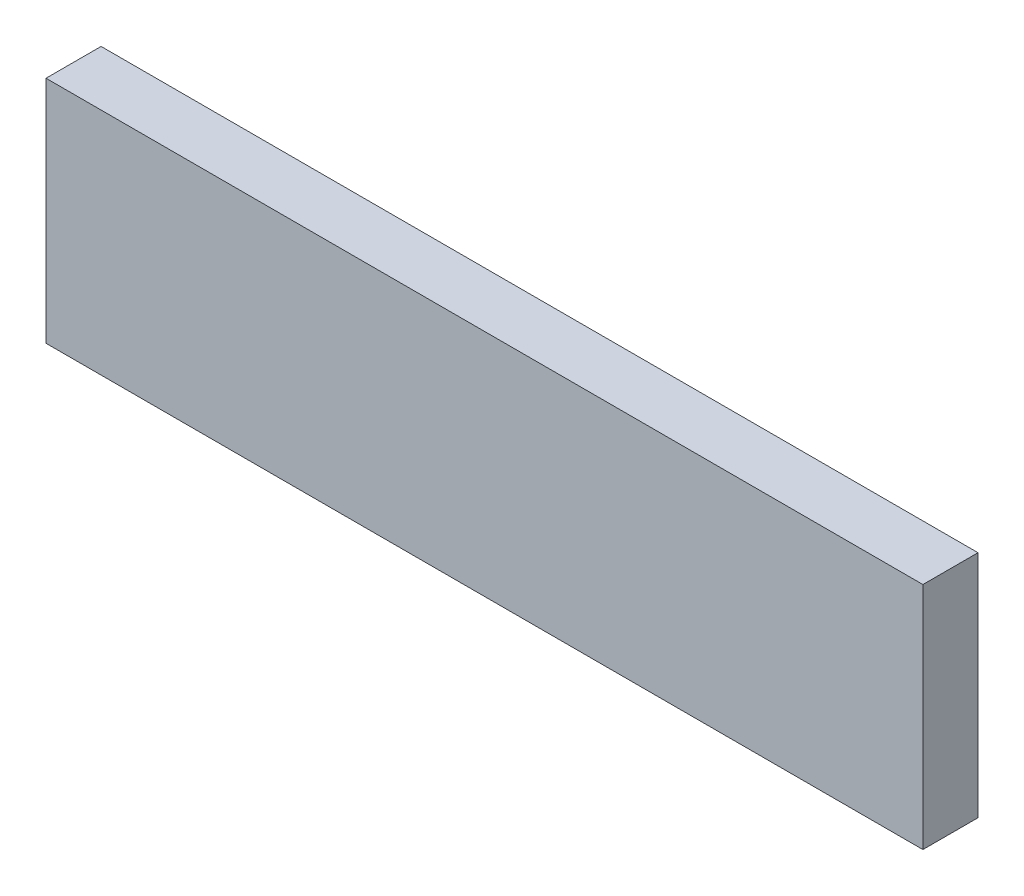
SolidWorks part; units mm, degrees
ref_plane "Plano frontal" through (0, 0, 0) normal (0, 0, 1) x (1, 0, 0)
ref_plane "Plano superior" through (0, 0, 0) normal (0, 1, 0) x (1, 0, 0)
ref_plane "Plano direito" through (0, 0, 0) normal (1, 0, 0) x (0, 0, -1)
sketch "Esboço1" plane through (0, 0, 0) normal (0, 0, 1) x (1, 0, 0)
  line L1 (-95.5, 25) -> (95.5, 25)
  line L2 (-95.5, 25) -> (-95.5, -25)
  line L3 (-95.5, -25) -> (95.5, -25)
  line L4 (95.5, 25) -> (95.5, -25)
  line L5 (-95.5, 25) -> (95.5, -25) construction
  line L6 (-95.5, -25) -> (95.5, 25) construction
  point P0 (0, 0)
extrude "Ressalto-extrusão1" add sketch "Esboço1" along normal mid plane 12
ref_plane "Plano1" through (0, -25, 0) normal (0, -1, 0) x (-1, 0, 0)
sketch "Esboço4" plane through (0, -25, 0) normal (0, -1, 0) x (-1, 0, 0)
  circle A0 centre (75, 0) radius 3
  circle A1 centre (-75, 0) radius 3
extrude "Corte-extrusão1" cut sketch "Esboço4" against normal blind 20
